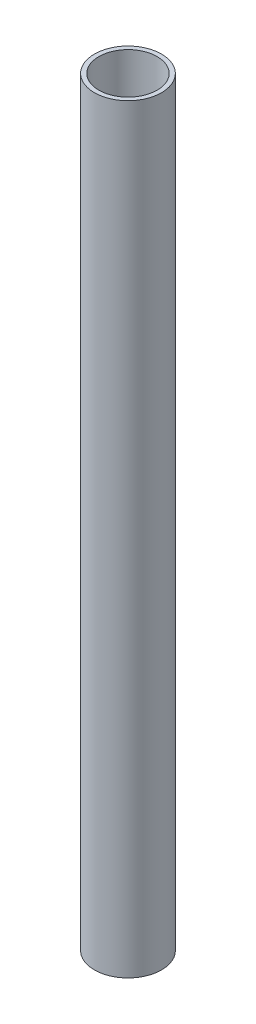
SolidWorks part; units mm, degrees
material "AISI 4130 Steel, normalized at 870C"
ref_plane "Front Plane" through (0, 0, 0) normal (0, 0, 1) x (1, 0, 0)
ref_plane "Top Plane" through (0, 0, 0) normal (0, 1, 0) x (1, 0, 0)
ref_plane "Right Plane" through (0, 0, 0) normal (1, 0, 0) x (0, 0, -1)
sketch "Sketch2" plane through (0, 0, 0) normal (0, 0, 1) x (1, 0, 0)
  line L0 (0, -133.35) -> (0, 133.35)
  dimension "D1" = 266.7
sketch "Sketch1" plane through (0, 0, 0) normal (0, 1, 0) x (1, 0, 0)
  circle A0 centre (0, 0) radius 9.525
  circle A1 centre (0, 0) radius 8.2804
  dimension "D1" = 19.05
  dimension "D2" = 1.2446
extrude "Boss-Extrude1" add sketch "Sketch1" along normal mid plane 215.9
